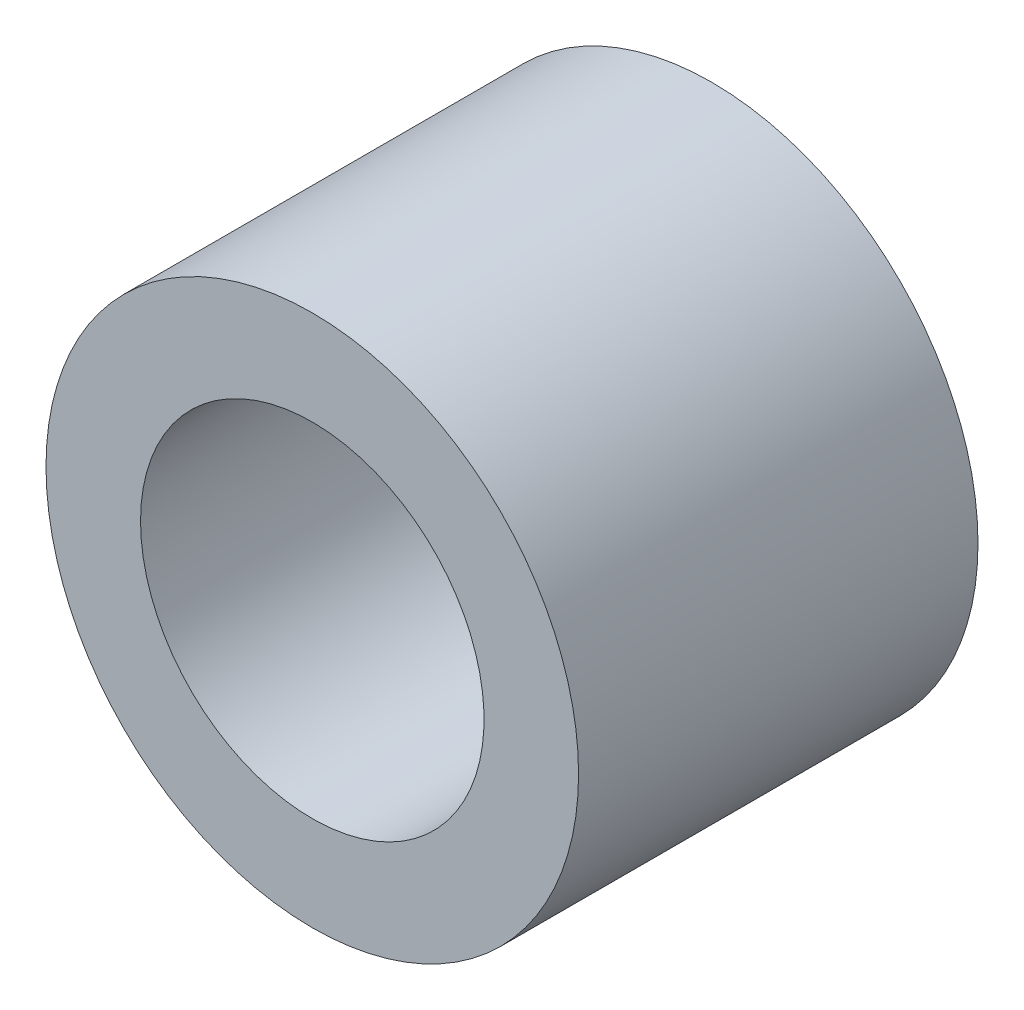
SolidWorks part; units mm, degrees
material "Nylon 6/10"
ref_plane "Front Plane" through (0, 0, 0) normal (0, 0, 1) x (1, 0, 0)
ref_plane "Top Plane" through (0, 0, 0) normal (0, 1, 0) x (1, 0, 0)
ref_plane "Right Plane" through (0, 0, 0) normal (1, 0, 0) x (0, 0, -1)
sketch "Sketch1" plane through (0, 0, 0) normal (0, 0, 1) x (1, 0, 0)
  circle A0 centre (0, 0) radius 2.54
  circle A1 centre (0, 0) radius 1.6383
  dimension "D1" = 3.2766
  dimension "D2" = 5.08
extrude "Extrude1" add sketch "Sketch1" along normal blind 3.81
